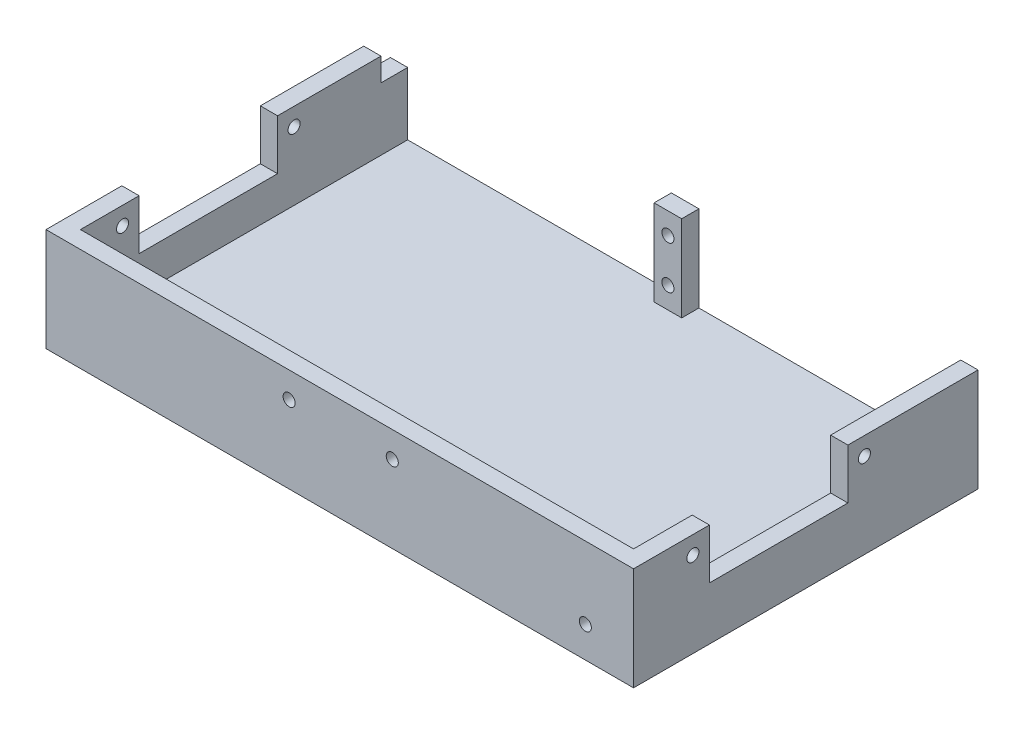
SolidWorks part; units mm, degrees
ref_plane "Front Plane" through (0, 0, 0) normal (0, 0, 1) x (1, 0, 0)
ref_plane "Top Plane" through (0, 0, 0) normal (0, 1, 0) x (1, 0, 0)
ref_plane "Right Plane" through (0, 0, 0) normal (1, 0, 0) x (0, 0, -1)
sketch "Sketch3" plane through (0, 0, 0) normal (0, 1, 0) x (1, 0, 0)
  line L1 (-78.8399, 13.5354) -> (91.7401, 13.5354)
  line L2 (-78.8399, 13.5354) -> (-78.8399, -86.4646)
  line L3 (-78.8399, -86.4646) -> (91.7401, -86.4646)
  line L4 (91.7401, 13.5354) -> (91.7401, -86.4646)
  point P4 (0, 0)
  point P5 (0, 0)
  point P6 (0, 0)
  point P7 (0, 0)
extrude "Boss-Extrude1" add sketch "Sketch3" along normal blind 5
sketch "Sketch4" plane through (0, 5, 0) normal (0, 1, 0) x (1, 0, 0)
  line L0 (91.7401, -86.4646) -> (91.7401, 13.5354)
  line L1 (-78.8399, -86.4646) -> (-78.8399, 13.5354)
  line L2 (-78.8399, 13.5354) -> (-73.8399, 13.5354)
  line L3 (-73.8399, 13.5354) -> (-73.8399, -86.4646)
  line L4 (-73.8399, -86.4646) -> (-78.8399, -86.4646)
  line L5 (91.7401, 13.5354) -> (86.7401, 13.5354)
  line L6 (91.7401, 13.5354) -> (-78.8399, 13.5354) construction
  line L7 (86.7401, 13.5354) -> (86.7401, -86.4646)
  line L8 (-78.8399, -86.4646) -> (91.7401, -86.4646) construction
  line L9 (86.7401, -86.4646) -> (91.7401, -86.4646)
  point P6 (0, 0)
  point P11 (0, 0)
extrude "Boss-Extrude2" add sketch "Sketch4" along normal blind 24.94
sketch "Sketch6" plane through (0, 5, 0) normal (0, 1, 0) x (1, 0, 0)
  line L3 (-73.8399, 13.5354) -> (-73.8399, -86.4646) construction
  line L4 (86.7401, -86.4646) -> (-73.8399, -86.4646)
  line L6 (86.7401, -86.4646) -> (86.7401, -81.4646)
  line L7 (86.7401, -81.4646) -> (-73.8399, -81.4646)
  line L8 (-73.8399, -86.4646) -> (-73.8399, -81.4646)
extrude "Boss-Extrude3" add sketch "Sketch6" along normal blind 24.94
sketch "Sketch7" plane through (0, 5, 0) normal (0, 1, 0) x (1, 0, 0)
  line L0 (6.4501, 13.5354) -> (2.7151, 13.5354)
  line L1 (86.7401, 13.5354) -> (-73.8399, 13.5354) construction
  line L2 (6.4501, 13.5354) -> (10.7151, 13.5354)
  line L3 (10.7151, 13.5354) -> (10.7151, 8.5354)
  line L4 (10.7151, 8.5354) -> (2.7151, 8.5354)
  line L5 (2.7151, 8.5354) -> (2.7151, 13.5354)
extrude "Boss-Extrude4" add sketch "Sketch7" along normal blind 24.94
sketch "Sketch8" plane through (0, 0, -8.5354) normal (0, 0, 1) x (1, 0, 0)
  line L0 (6.7151, 5) -> (6.7151, 29.94) construction
  line L1 (2.7151, 5) -> (10.7151, 5) construction
  line L2 (2.7151, 29.94) -> (10.7151, 29.94) construction
  line L3 (6.7151, 17.47) -> (2.7151, 17.47) construction
  line L4 (2.7151, 29.94) -> (2.7151, 5) construction
  line L5 (6.7151, 5) -> (6.7151, 17.47) construction
  line L6 (6.7151, 17.47) -> (6.7151, 29.94) construction
  circle A0 centre (6.7151, 11.235) radius 1.75
  circle A1 centre (6.7151, 23.705) radius 1.75
extrude "Cut-Extrude1" cut sketch "Sketch8" against normal blind 8
sketch "Sketch9" plane through (-78.8399, 0, 0) normal (-1, 0, 0) x (0, 0, 1)
  line L0 (-13.5354, 29.94) -> (-13.5354, 23.2) construction
  line L1 (-13.5354, 29.94) -> (-13.5354, 0) construction
  line L2 (-13.5354, 23.2) -> (-5.7854, 23.2) construction
  line L3 (-5.7854, 23.2) -> (-5.7854, 29.94) construction
  line L4 (-13.5354, 29.94) -> (86.4646, 29.94) construction
  line L5 (-13.5354, 29.94) -> (-13.5354, 23.2)
  line L6 (-13.5354, 23.2) -> (-5.7854, 23.2)
  line L7 (-5.7854, 23.2) -> (-5.7854, 29.94)
  line L8 (-5.7854, 29.94) -> (-13.5354, 29.94)
extrude "Cut-Extrude2" cut sketch "Sketch9" against normal blind 10
sketch "Sketch12" plane through (-78.8399, 0, 0) normal (-1, 0, 0) x (0, 0, 1)
  line L0 (40.3396, 29.94) -> (64.4396, 29.94) construction
  line L1 (-5.7854, 29.94) -> (86.4646, 29.94) construction
  line L2 (40.3396, 29.94) -> (24.2396, 29.94) construction
  line L3 (24.2396, 29.94) -> (24.2396, 15.375) construction
  line L4 (24.2396, 15.375) -> (64.4396, 15.375) construction
  line L5 (64.4396, 15.375) -> (64.4396, 29.94) construction
  line L6 (64.4396, 29.94) -> (24.2396, 29.94)
  line L7 (24.2396, 29.94) -> (24.2396, 15.375)
  line L8 (24.2396, 15.375) -> (64.4396, 15.375)
  line L9 (64.4396, 15.375) -> (64.4396, 29.94)
extrude "Cut-Extrude4" cut sketch "Sketch12" against normal blind 200
sketch "Sketch13" plane through (-78.8399, 0, 0) normal (-1, 0, 0) x (0, 0, 1)
  circle A0 centre (69.2396, 24.75) radius 1.75
  circle A1 centre (19.4396, 24.75) radius 1.75
extrude "Cut-Extrude5" cut sketch "Sketch13" against normal blind 200
sketch "Sketch14" plane through (0, 0, 86.4646) normal (0, 0, 1) x (1, 0, 0)
  line L0 (-78.8399, 29.94) -> (6.4501, 29.94) construction
  line L1 (-78.8399, 29.94) -> (91.7401, 29.94) construction
  line L2 (6.4501, 29.94) -> (-3.2549, 29.94) construction
  line L3 (-3.2549, 29.94) -> (16.6869, 29.94) construction
  line L4 (-3.2549, 29.94) -> (-3.2549, 0) construction
  line L5 (-78.8399, 0) -> (91.7401, 0) construction
  line L6 (-3.2549, 0) -> (-13.2549, 0) construction
  line L7 (-13.2549, 0) -> (-13.2549, 29.94) construction
  line L8 (-13.2549, 29.94) -> (-3.2549, 29.94) construction
  line L9 (16.6869, 29.94) -> (26.6889, 29.94) construction
  line L10 (26.6889, 29.94) -> (26.6889, 0) construction
  line L11 (26.6889, 0) -> (16.6851, 0) construction
  line L12 (16.6869, 14.94) -> (-3.2549, 14.97) construction
  line L13 (16.6869, 29.94) -> (16.6869, 14.94) construction
  line L14 (-3.2549, 14.97) -> (-13.2549, 14.97) construction
  line L15 (21.6879, 14.94) -> (21.6879, 29.94) construction
  line L16 (-13.2549, 14.97) -> (-8.2549, 14.97) construction
  line L17 (-52.8499, 9) -> (80.0001, 9) construction
  line L19 (80.0001, 9) -> (77.7401, 9) construction
  line L20 (-78.8399, 9) -> (-52.8499, 9) construction
  line L21 (-78.8399, 29.94) -> (-78.8399, 0) construction
  line L22 (80.0001, 9) -> (77.7401, 9) construction
  circle A0 centre (21.6879, 22.44) radius 1.75
  circle A1 centre (-8.2521, 22.44) radius 1.75
  circle A3 centre (77.7401, 9) radius 1.75
  point P28 (0, 0)
extrude "Cut-Extrude6" cut sketch "Sketch14" against normal blind 10
